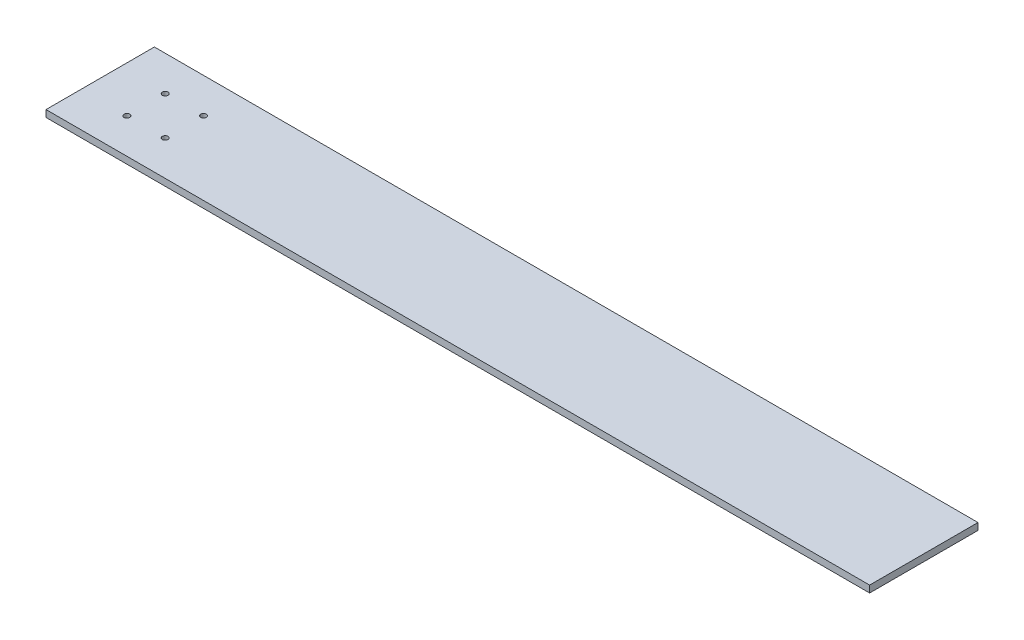
SolidWorks part; units mm, degrees
ref_plane "Front Plane" through (0, 0, 0) normal (0, 0, 1) x (1, 0, 0)
ref_plane "Top Plane" through (0, 0, 0) normal (0, 1, 0) x (1, 0, 0)
ref_plane "Right Plane" through (0, 0, 0) normal (1, 0, 0) x (0, 0, -1)
sketch "Sketch1" plane through (0, 0, 0) normal (0, 1, 0) x (1, 0, 0)
  line L1 (0, 0) -> (760, 0)
  line L2 (0, 0) -> (0, 100)
  line L3 (0, 100) -> (760, 100)
  line L4 (760, 0) -> (760, 100)
  dimension "D1" = 760
  dimension "D2" = 100
extrude "Boss-Extrude1" add sketch "Sketch1" along normal blind 6.35
sketch "Sketch2" plane through (0, 6.35, 0) normal (0, 1, 0) x (1, 0, 0)
  line L0 (42.3225, 67.6775) -> (77.6775, 67.6775) construction
  line L1 (42.3225, 67.6775) -> (42.3225, 32.3225) construction
  line L2 (42.3225, 32.3225) -> (77.6775, 67.6775) construction
  line L3 (42.3225, 67.6775) -> (77.6775, 32.3225) construction
  line L4 (0, 100) -> (0, 0) construction
  line L6 (60, 100) -> (60, 0) construction
  line L7 (0, 100) -> (760, 100) construction
  line L8 (0, 0) -> (760, 0) construction
  circle A0 centre (42.3225, 67.6775) radius 2.625
  circle A1 centre (77.6775, 67.6775) radius 2.625
  circle A2 centre (77.6775, 32.3225) radius 2.625
  circle A3 centre (42.3225, 32.3225) radius 2.625
  point P2 (60, 50)
  point P18 (60, 50)
  dimension "D1" = 5.25
  dimension "D4" = 35.355
  dimension "D5" = 35.355
  dimension "D6" = 60
  dimension "D2" = 2
  dimension "D3" = 2
extrude "Cut-Extrude1" cut sketch "Sketch2" against normal through all
